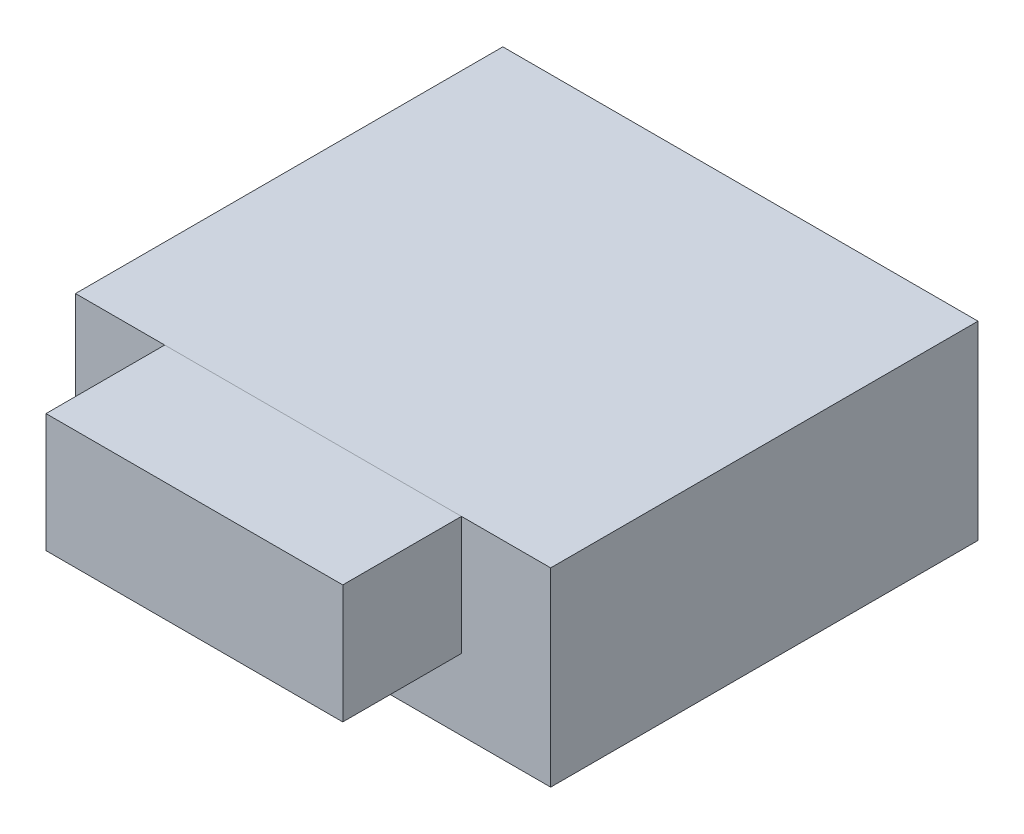
SolidWorks part; units mm, degrees
ref_plane "Front Plane" through (0, 0, 0) normal (0, 0, 1) x (1, 0, 0)
ref_plane "Top Plane" through (0, 0, 0) normal (0, 1, 0) x (1, 0, 0)
ref_plane "Right Plane" through (0, 0, 0) normal (1, 0, 0) x (0, 0, -1)
sketch "Sketch1" plane through (0, 0, 0) normal (0, 1, 0) x (1, 0, 0)
  line L1 (2.0015, -1.8) -> (-2.0015, -1.8)
  line L2 (2.0015, -1.8) -> (2.0015, 1.8)
  line L3 (2.0015, 1.8) -> (-2.0015, 1.8)
  line L4 (-2.0015, -1.8) -> (-2.0015, 1.8)
  line L5 (2.0015, -1.8) -> (-2.0015, 1.8) construction
  line L6 (2.0015, 1.8) -> (-2.0015, -1.8) construction
  point P0 (0, 0)
  dimension "D1" = 4.003
  dimension "D2" = 3.6
extrude "Boss-Extrude1" add sketch "Sketch1" along normal blind 1.6
sketch "Sketch2" plane through (0, 0, 1.8) normal (0, 0, 1) x (1, 0, 0)
  line L0 (0, -0.88) -> (0, 0.88) construction
  line L1 (1.25, 0.6) -> (-1.25, 0.6)
  line L2 (1.25, 0.6) -> (1.25, 1.6)
  line L3 (1.25, 1.6) -> (-1.25, 1.6)
  line L4 (-1.25, 0.6) -> (-1.25, 1.6)
  line L5 (1.25, 0.6) -> (-1.25, 1.6) construction
  line L6 (1.25, 1.6) -> (-1.25, 0.6) construction
  line L7 (-2.0015, 1.6) -> (2.0015, 1.6) construction
  point P0 (0, 1.1)
  dimension "D1" = 2.5
  dimension "D2" = 1
extrude "Boss-Extrude2" add sketch "Sketch2" along normal blind 1 separate body
sketch "Sketch3" plane through (0, 0, 0) normal (0, -1, 0) x (1, 0, 0)
  line L0 (0, 0) -> (0, 3.5671)
  line L1 (0, -0.88) -> (0, 0.88) construction
